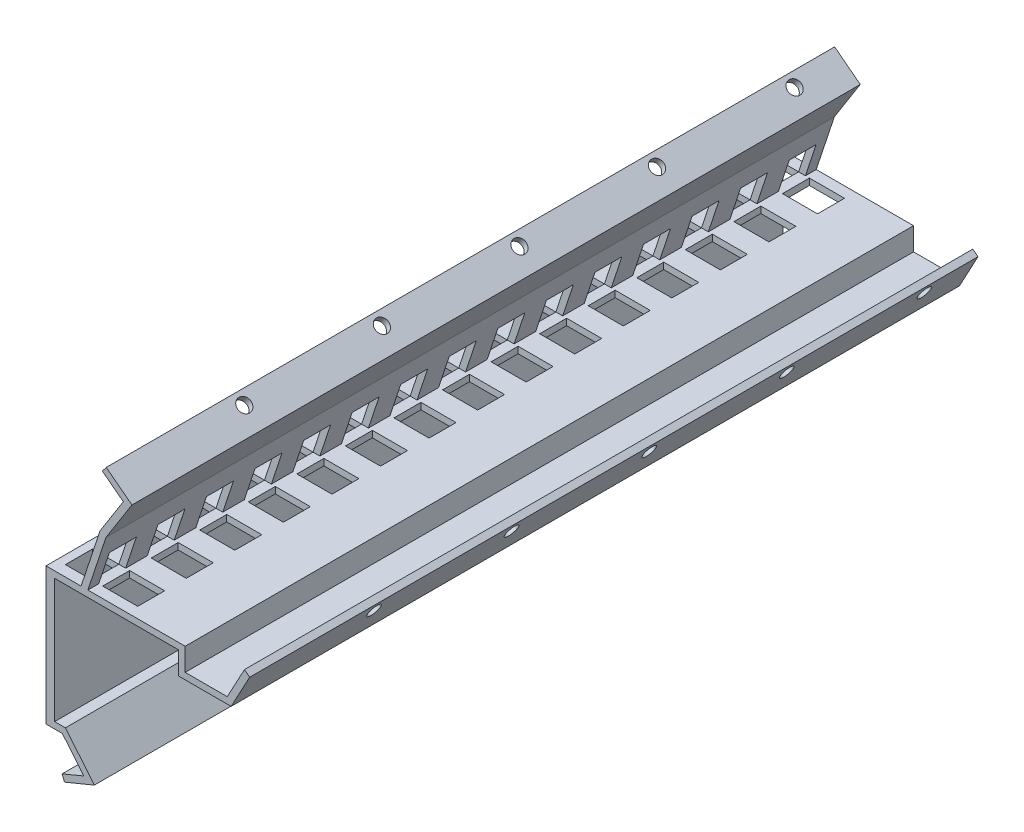
SolidWorks part; units mm, degrees
ref_plane "Front Plane" through (0, 0, 0) normal (0, 0, 1) x (1, 0, 0)
ref_plane "Top Plane" through (0, 0, 0) normal (0, 1, 0) x (1, 0, 0)
ref_plane "Right Plane" through (0, 0, 0) normal (1, 0, 0) x (0, 0, -1)
sketch "Sketch1" plane through (0, 0, 0) normal (0, 0, 1) x (1, 0, 0)
  line L0 (0, 0) -> (2, 0)
  line L1 (0, 0) -> (0, 23)
  line L2 (0, 23) -> (23, 23)
  line L6 (24.2, 24.2) -> (6.164, 24.2)
  line L7 (6.164, 24.2) -> (9.5163, 34.3338)
  line L9 (8.4234, 34.8509) -> (4.9, 24.2)
  line L10 (4.9, 24.2) -> (-1.6, 24.2)
  line L11 (-1.6, 24.2) -> (-1.6, -1.2)
  line L12 (-1.6, -1.2) -> (1.4329, -1.2)
  line L14 (23, 23) -> (23, 18.8)
  line L15 (23, 18.8) -> (32.7151, 18.8)
  line L16 (24.2, 24.2) -> (24.2, 20)
  line L17 (24.2, 20) -> (31.9971, 20)
  line L18 (31.9971, 20) -> (35.1828, 25.9373)
  line L20 (36.1475, 25.1971) -> (32.7151, 18.8)
  line L25 (53.9979, 11.5) -> (8.753, 46.2177) construction
  line L26 (53.9979, 11.5) -> (1.3091, -10.3244) construction
  line L31 (35.1828, 25.9373) -> (36.1475, 25.1971)
  line L35 (14.1924, 40.5313) -> (32.8248, 26.2341) construction
  line L36 (9.5163, 34.3338) -> (14.3303, 41.9381)
  line L37 (14.3303, 41.9381) -> (9.5702, 45.5906)
  line L38 (9.5702, 45.5906) -> (8.8396, 44.6386)
  line L39 (8.8396, 44.6386) -> (12.7299, 41.6535)
  line L40 (12.7299, 41.6535) -> (8.4234, 34.8509)
  line L41 (2, 0) -> (7.358, -6.52)
  line L48 (1.3898, -7.6933) -> (5.4029, -6.031)
  line L49 (5.4029, -6.031) -> (1.4329, -1.2)
  line L50 (1.3898, -7.6933) -> (1.8133, -8.8167)
  line L51 (1.8133, -8.8167) -> (7.358, -6.52)
  circle A0 centre (53.9979, 11.5) radius 57.03 construction
  circle A1 centre (53.9979, 11.5) radius 50 construction
  circle A2 centre (53.9979, 11.5) radius 22.5 construction
  circle A3 centre (53.9979, 11.5) radius 23.7159 construction
  circle A4 centre (53.9979, 11.5) radius 56 construction
  point P31 (10.5766, 38.2522)
  point P32 (1, 0)
  dimension "D21" = 114.06
  dimension "D14" = 100
  dimension "D8" = 45
  dimension "D1" = 2
  dimension "D2" = 23
  dimension "D3" = 23
  dimension "D4" = 1.2
  dimension "D5" = 1.2
  dimension "D6" = 1.6
  dimension "D7" = 1.2
  dimension "D9" = 6.5
  dimension "D10" = 4.2
  dimension "D11" = 1.2
  dimension "D12" = 1.2
  dimension "D13" = 1.2
  dimension "D15" = 1.2
  dimension "D16" = 6
  dimension "D17" = 1.2
  dimension "D18" = 9
  dimension "D19" = 1.2
  dimension "D20" = 1.2
  dimension "D22" = 60
  dimension "D23" = 22.5
  dimension "D24" = 1.2
  dimension "D25" = 1.2
  dimension "D26" = 4.3438
extrude "Boss-Extrude1" add sketch "Sketch1" along normal mid plane 171
sketch "Sketch2" plane through (-1.6, 0, 0) normal (-1, 0, 0) x (0, 0, 1)
  line L0 (81, 30.2) -> (81, 14.3801) construction
  line L1 (78.5, 21.2) -> (83.5, 21.2)
  line L2 (78.5, 21.2) -> (78.5, 30.2)
  line L3 (78.5, 30.2) -> (83.5, 30.2)
  line L4 (83.5, 21.2) -> (83.5, 30.2)
  line L5 (85.5, 24.2) -> (-85.5, 24.2) construction
  dimension "D1" = 4.5
  dimension "D2" = 5
  dimension "D3" = 3
  dimension "D4" = 9
extrude "Cut-Extrude1" cut sketch "Sketch2" against normal blind 15
pattern_linear "LPattern2" count 19 spacing 9 along (0, 0, -1) of "Cut-Extrude1"
sketch "Sketch3" plane through (2.9235, -7.058, 0) normal (-0.3827, 0.9239, 0) x (0.9239, 0.3827, 0)
  line L0 (2.6837, -85.5) -> (-1.6601, -85.5) construction
  line L1 (-1.6601, -85.5) -> (-1.6601, 85.5) construction
  circle A0 centre (0.3399, -76.5) radius 1.25
  dimension "D2" = 2
  dimension "D3" = 2.5
  dimension "D1" = 9
extrude "Cut-Extrude2" cut sketch "Sketch3" against normal blind 12
sketch "Sketch4" plane through (24.8347, 32.3652, 0) normal (-0.6088, -0.7934, 0) x (0.7934, -0.6088, 0)
  line L0 (-20.1613, 85.5) -> (-15.2578, 85.5) construction
  line L1 (-20.1613, 85.5) -> (-20.1613, -85.5) construction
  circle A0 centre (-18.1613, 76.5) radius 1.25
  dimension "D1" = 9
  dimension "D2" = 2
  dimension "D3" = 2.5
extrude "Cut-Extrude3" cut sketch "Sketch4" against normal blind 12
sketch "Sketch5" plane through (17.5697, -9.4271, 0) normal (0.8812, -0.4728, 0) x (0, 0, -1)
  line L0 (-85.5, 32.0336) -> (-85.5, 39.2934) construction
  line L1 (-85.5, 39.2934) -> (85.5, 39.2934) construction
  circle A0 centre (-76.5, 37.2934) radius 1.25
  dimension "D1" = 9
  dimension "D2" = 2.5
  dimension "D3" = 2
extrude "Cut-Extrude4" cut sketch "Sketch5" against normal blind 5
pattern_linear "LPattern3" count 7 spacing 25.5 along (0, 0, -1) of "Cut-Extrude2", "Cut-Extrude3", "Cut-Extrude4"
sketch "Sketch6" plane through (0, 0, 85.5) normal (0, 0, 1) x (1, 0, 0)
  line L1 (4.9, 24.2) -> (6.9, 24.2)
  line L2 (4.9, 24.2) -> (4.9, 23)
  line L3 (4.9, 23) -> (6.9, 23)
  line L4 (6.9, 24.2) -> (6.9, 23)
  line L5 (-1.6, 24.2) -> (0, 24.2)
  line L6 (-1.6, 24.2) -> (-1.6, 21.2)
  line L7 (-1.6, 21.2) -> (0, 21.2)
  line L8 (0, 24.2) -> (0, 21.2)
  line L10 (0, 23) -> (13.4, 23)
  line L11 (13.4, 23) -> (13.4, 24.2)
  line L12 (13.4, 24.2) -> (6.164, 24.2)
  line L13 (6.164, 24.2) -> (8.1488, 30.2)
  line L14 (8.1488, 30.2) -> (6.8848, 30.2)
  line L15 (6.8848, 30.2) -> (4.9, 24.2)
  line L16 (4.9, 24.2) -> (-1.6, 24.2)
  line L17 (-1.6, 24.2) -> (-1.6, 21.2)
  line L18 (-1.6, 21.2) -> (0, 21.2)
  line L19 (0, 21.2) -> (0, 23)
  line L20 (0, 23) -> (13.4, 23) construction
  line L21 (13.4, 23) -> (13.4, 24.2) construction
  line L22 (13.4, 24.2) -> (6.164, 24.2) construction
  line L23 (6.164, 24.2) -> (8.1488, 30.2) construction
  line L24 (8.1488, 30.2) -> (6.8848, 30.2) construction
  line L25 (6.8848, 30.2) -> (4.9, 24.2) construction
  line L26 (4.9, 24.2) -> (-1.6, 24.2) construction
  line L27 (-1.6, 24.2) -> (-1.6, 21.2) construction
  line L28 (-1.6, 21.2) -> (0, 21.2) construction
  line L29 (0, 21.2) -> (0, 23) construction
  dimension "D2" = 2
  dimension "D1" = 0
extrude "Boss-Extrude2" add sketch "Sketch6" against normal through all
sketch "Sketch7" plane through (0, 0, 85.5) normal (0, 0, 1) x (1, 0, 0)
  line L1 (49.3452, 49.2665) -> (-25.4946, 49.2665)
  line L2 (49.3452, 49.2665) -> (49.3452, -12.5791)
  line L3 (49.3452, -12.5791) -> (-25.4946, -12.5791)
  line L4 (-25.4946, 49.2665) -> (-25.4946, -12.5791)
extrude "Cut-Extrude5" cut sketch "Sketch7" against normal blind 36
